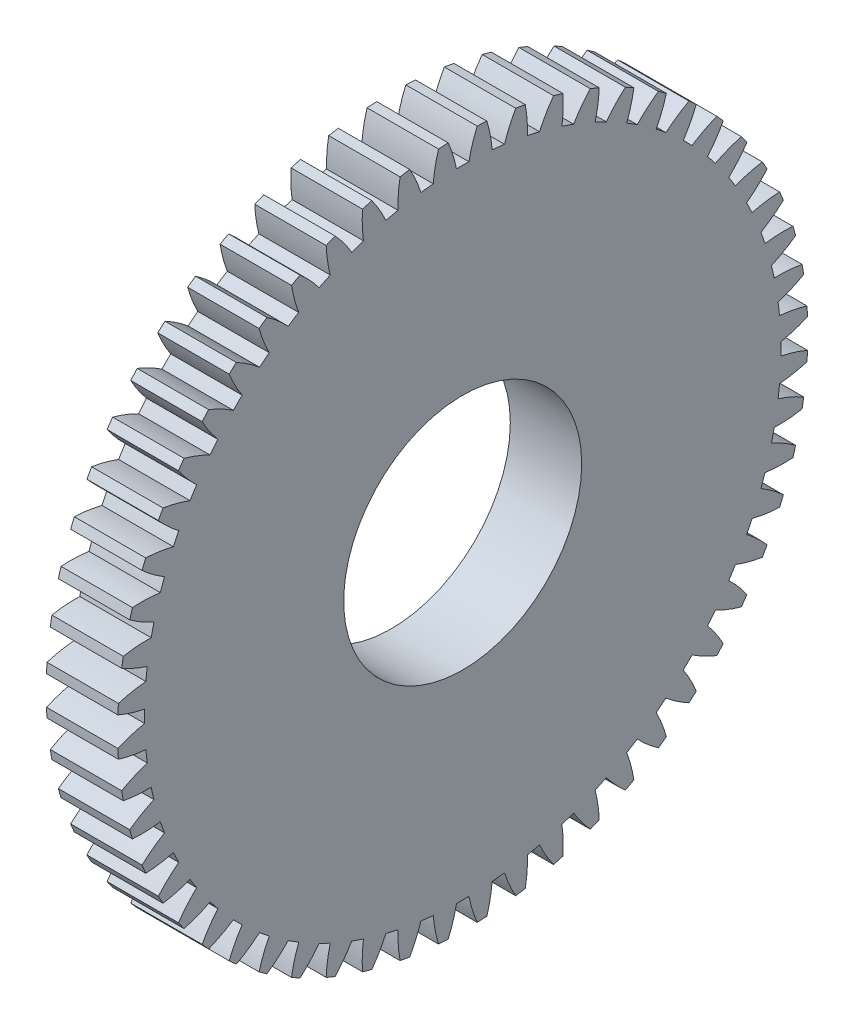
SolidWorks part; units mm, degrees
material "ABS PC"
ref_plane "Plane1" through (0, 0, 0) normal (0, 0, 1) x (1, 0, 0)
ref_plane "Plane2" through (0, 0, 0) normal (0, 1, 0) x (1, 0, 0)
ref_plane "Plane3" through (0, 0, 0) normal (1, 0, 0) x (0, 0, -1)
sketch "BasProSke" plane through (0, 0, 0) normal (0, 1, 0) x (1, 0, 0)
  line L0 (-10, 0) -> (60, 0) construction
  line L1 (0, 0) -> (0, 23.0188)
  line L2 (0, 0) -> (4.7625, 0)
  line L3 (4.7625, 0) -> (4.7625, 23.0187)
  line L4 (4.7625, 23.0187) -> (0, 23.0188)
  dimension "Diameter" = 46.0375
  dimension "Thickness" = 4.7625
revolve "Base-Revolve" add sketch "BasProSke" angle 360 about L0
sketch "TooCutSke" plane through (0, 0, 0) normal (1, 0, 0) x (0, 0, -1)
  line L1 (0, 0) -> (0, 107) construction
  line L2 (0, 0) -> (-0.6731, 22.2148) construction
  line L3 (0, 0) -> (-2.4915, 44.3653) construction
  line L4 (-0.6731, 22.2148) -> (-1.2458, 22.1826) construction
  arc A0 (0.4138, 21.2177) -> (-0.4138, 21.2177) centre (0, 0) ccw
  arc A1 (0.9784, 23.0234) -> (-0.9784, 23.0234) centre (0, 0) ccw
  circle A2 centre (0, 0) radius 22.225 construction
  circle A3 centre (0, 0) radius 21.5171 construction
  arc A4 (-0.4138, 21.2177) -> (-0.9784, 23.0234) centre (-9.1329, 19.4827) ccw
  arc A5 (0.9784, 23.0234) -> (0.4138, 21.2177) centre (9.1329, 19.4827) ccw
  dimension "Root_dia" = 42.4434
  dimension "Overcut_dia" = 46.0883
  dimension "Pitch_dia" = 44.45
  dimension "Base_dia" = 43.0342
  dimension "Flank_rad" = 8.89
  dimension "Half_ang" = 3.214
  dimension "Half_CT" = 0.5735
extrude "ToothCut" cut sketch "TooCutSke" along normal through all
pattern_circular "TeethCuts" count 56 every 6.429 about axis through (-10, 0, 0) along (1, 0, 0) of "ToothCut"
sketch "BorSke" plane through (0, 0, 0) normal (1, 0, 0) x (0, 0, -1)
  circle A0 centre (0, 0) radius 3.175
  dimension "Diameter" = 6.35
extrude "Bore" cut sketch "BorSke" along normal mid plane 22.2255
sketch "Sketch1" plane through (4.7625, 0, 0) normal (1, 0, 0) x (0, 0, -1)
  circle A0 centre (0, 0) radius 7.9375
  dimension "D1" = 15.875
extrude "Cut-Extrude1" cut sketch "Sketch1" against normal through all
equation "\"Num_teeth@TeethCuts\" = ((sgn( \"Num_teeth@TeethCuts\" - 2.0)+1)*( \"Num_teeth@TeethCuts\" - 2.0))/2 +2.0"
